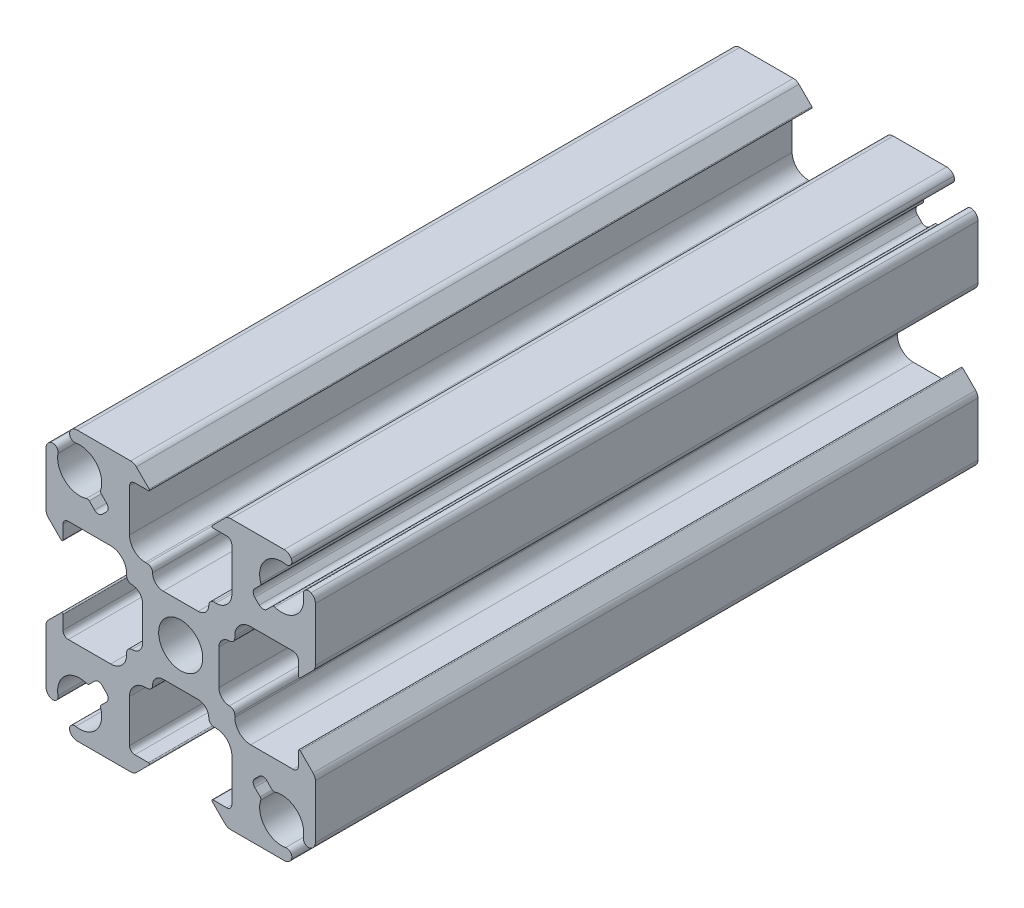
SolidWorks part; units mm, degrees
ref_plane "Front Plane" through (0, 0, 0) normal (0, 0, 1) x (1, 0, 0)
ref_plane "Top Plane" through (0, 0, 0) normal (0, 1, 0) x (1, 0, 0)
ref_plane "Right Plane" through (0, 0, 0) normal (1, 0, 0) x (0, 0, -1)
ref_plane "Plane1" through (0, 0, 0) normal (0, 0, -1) x (-1, 0, 0)
sketch "Sketch1" plane through (0, 0, 0) normal (0, 0, -1) x (-1, 0, 0)
  line L0 (-7.4885, 8.6199) -> (-6.9856, 8.117)
  line L1 (-6.9856, 7.4099) -> (-7.4099, 6.9856)
  line L2 (-8.117, 6.9856) -> (-8.6199, 7.4885)
  line L3 (-12.7, 9.7594) -> (-12.7, 4.7107)
  line L4 (-12.4803, 4.1803) -> (-11.2707, 2.9707)
  line L5 (-11.1, 3.0414) -> (-11.1, 4.325)
  line L6 (-10.6, 4.825) -> (-6.6, 4.825)
  line L7 (-5.1, 3.325) -> (-5.1, 3.15)
  line L8 (-3.6, 1.65) -> (-3.6, -1.65)
  line L9 (-5.1, -3.15) -> (-5.1, -3.325)
  line L10 (-6.6, -4.825) -> (-10.6, -4.825)
  line L11 (-11.1, -4.325) -> (-11.1, -3.0414)
  line L12 (-11.2707, -2.9707) -> (-12.4803, -4.1803)
  line L13 (-12.7, -4.7107) -> (-12.7, -9.7594)
  line L14 (-8.6199, -7.4885) -> (-8.117, -6.9856)
  line L15 (-7.4099, -6.9856) -> (-6.9856, -7.4099)
  line L16 (-6.9856, -8.117) -> (-7.4885, -8.6199)
  line L17 (-9.7594, -12.7) -> (-4.7107, -12.7)
  line L18 (-4.1803, -12.4803) -> (-2.9707, -11.2707)
  line L19 (-3.0414, -11.1) -> (-4.325, -11.1)
  line L20 (-4.825, -10.6) -> (-4.825, -6.6)
  line L21 (-3.325, -5.1) -> (-3.15, -5.1)
  line L22 (-1.65, -3.6) -> (1.65, -3.6)
  line L23 (3.15, -5.1) -> (3.325, -5.1)
  line L24 (4.825, -6.6) -> (4.825, -10.6)
  line L25 (4.325, -11.1) -> (3.0414, -11.1)
  line L26 (2.9707, -11.2707) -> (4.1803, -12.4803)
  line L27 (4.7107, -12.7) -> (9.7594, -12.7)
  line L28 (7.4885, -8.6199) -> (6.9856, -8.117)
  line L29 (6.9856, -7.4099) -> (7.4099, -6.9856)
  line L30 (8.117, -6.9856) -> (8.6199, -7.4885)
  line L31 (12.7, -9.7594) -> (12.7, -4.7107)
  line L32 (12.4803, -4.1803) -> (11.2707, -2.9707)
  line L33 (11.1, -3.0414) -> (11.1, -4.325)
  line L34 (10.6, -4.825) -> (6.6, -4.825)
  line L35 (5.1, -3.325) -> (5.1, -3.15)
  line L36 (3.6, -1.65) -> (3.6, 1.65)
  line L37 (5.1, 3.15) -> (5.1, 3.325)
  line L38 (6.6, 4.825) -> (10.6, 4.825)
  line L39 (11.1, 4.325) -> (11.1, 3.0414)
  line L40 (11.2707, 2.9707) -> (12.4803, 4.1803)
  line L41 (12.7, 4.7107) -> (12.7, 9.7594)
  line L42 (8.6199, 7.4885) -> (8.117, 6.9856)
  line L43 (7.4099, 6.9856) -> (6.9856, 7.4099)
  line L44 (6.9856, 8.117) -> (7.4885, 8.6199)
  line L45 (9.7594, 12.7) -> (4.7107, 12.7)
  line L46 (4.1803, 12.4803) -> (2.9707, 11.2707)
  line L47 (3.0414, 11.1) -> (4.325, 11.1)
  line L48 (4.825, 10.6) -> (4.825, 6.6)
  line L49 (3.325, 5.1) -> (3.15, 5.1)
  line L50 (1.65, 3.6) -> (-1.65, 3.6)
  line L51 (-3.15, 5.1) -> (-3.325, 5.1)
  line L52 (-4.825, 6.6) -> (-4.825, 10.6)
  line L53 (-4.325, 11.1) -> (-3.0414, 11.1)
  line L54 (-2.9707, 11.2707) -> (-4.1803, 12.4803)
  line L55 (-4.7107, 12.7) -> (-9.7594, 12.7)
  circle A0 centre (0, 0) radius 2.08
  arc A1 (-9.7594, 12.7) -> (-10.4266, 12.2927) centre (-9.7594, 11.95) ccw
  arc A2 (-10.4266, 12.2927) -> (-9.8933, 11.5721) centre (-9.9818, 12.0642) ccw
  arc A3 (-9.8933, 11.5721) -> (-7.5492, 8.8748) centre (-9.525, 9.525) cw
  arc A4 (-7.5492, 8.8748) -> (-7.4885, 8.6199) centre (-7.3118, 8.7967) ccw
  arc A5 (-6.9856, 8.117) -> (-6.9856, 7.4099) centre (-7.3392, 7.7635) cw
  arc A6 (-7.4099, 6.9856) -> (-8.117, 6.9856) centre (-7.7635, 7.3392) cw
  arc A7 (-8.6199, 7.4885) -> (-8.8748, 7.5492) centre (-8.7967, 7.3118) ccw
  arc A8 (-8.8748, 7.5492) -> (-11.5721, 9.8933) centre (-9.525, 9.525) cw
  arc A9 (-11.5721, 9.8933) -> (-12.2927, 10.4266) centre (-12.0642, 9.9818) ccw
  arc A10 (-12.2927, 10.4266) -> (-12.7, 9.7594) centre (-11.95, 9.7594) ccw
  arc A11 (-12.7, 4.7107) -> (-12.4803, 4.1803) centre (-11.95, 4.7107) ccw
  arc A12 (-11.2707, 2.9707) -> (-11.1, 3.0414) centre (-11.2, 3.0414) ccw
  arc A13 (-11.1, 4.325) -> (-10.6, 4.825) centre (-10.6, 4.325) cw
  arc A14 (-6.6, 4.825) -> (-5.1, 3.325) centre (-6.6, 3.325) cw
  arc A15 (-5.1, 3.15) -> (-4.6, 2.65) centre (-4.6, 3.15) ccw
  arc A16 (-4.6, 2.65) -> (-3.6, 1.65) centre (-4.6, 1.65) cw
  arc A17 (-3.6, -1.65) -> (-4.6, -2.65) centre (-4.6, -1.65) cw
  arc A18 (-4.6, -2.65) -> (-5.1, -3.15) centre (-4.6, -3.15) ccw
  arc A19 (-5.1, -3.325) -> (-6.6, -4.825) centre (-6.6, -3.325) cw
  arc A20 (-10.6, -4.825) -> (-11.1, -4.325) centre (-10.6, -4.325) cw
  arc A21 (-11.1, -3.0414) -> (-11.2707, -2.9707) centre (-11.2, -3.0414) ccw
  arc A22 (-12.4803, -4.1803) -> (-12.7, -4.7107) centre (-11.95, -4.7107) ccw
  arc A23 (-12.7, -9.7594) -> (-12.2927, -10.4266) centre (-11.95, -9.7594) ccw
  arc A24 (-12.2927, -10.4266) -> (-11.5721, -9.8933) centre (-12.0642, -9.9818) ccw
  arc A25 (-11.5721, -9.8933) -> (-8.8748, -7.5492) centre (-9.525, -9.525) cw
  arc A26 (-8.8748, -7.5492) -> (-8.6199, -7.4885) centre (-8.7967, -7.3118) ccw
  arc A27 (-8.117, -6.9856) -> (-7.4099, -6.9856) centre (-7.7635, -7.3392) cw
  arc A28 (-6.9856, -7.4099) -> (-6.9856, -8.117) centre (-7.3392, -7.7635) cw
  arc A29 (-7.4885, -8.6199) -> (-7.5492, -8.8748) centre (-7.3118, -8.7967) ccw
  arc A30 (-7.5492, -8.8748) -> (-9.8933, -11.5721) centre (-9.525, -9.525) cw
  arc A31 (-9.8933, -11.5721) -> (-10.4266, -12.2927) centre (-9.9818, -12.0642) ccw
  arc A32 (-10.4266, -12.2927) -> (-9.7594, -12.7) centre (-9.7594, -11.95) ccw
  arc A33 (-4.7107, -12.7) -> (-4.1803, -12.4803) centre (-4.7107, -11.95) ccw
  arc A34 (-2.9707, -11.2707) -> (-3.0414, -11.1) centre (-3.0414, -11.2) ccw
  arc A35 (-4.325, -11.1) -> (-4.825, -10.6) centre (-4.325, -10.6) cw
  arc A36 (-4.825, -6.6) -> (-3.325, -5.1) centre (-3.325, -6.6) cw
  arc A37 (-3.15, -5.1) -> (-2.65, -4.6) centre (-3.15, -4.6) ccw
  arc A38 (-2.65, -4.6) -> (-1.65, -3.6) centre (-1.65, -4.6) cw
  arc A39 (1.65, -3.6) -> (2.65, -4.6) centre (1.65, -4.6) cw
  arc A40 (2.65, -4.6) -> (3.15, -5.1) centre (3.15, -4.6) ccw
  arc A41 (3.325, -5.1) -> (4.825, -6.6) centre (3.325, -6.6) cw
  arc A42 (4.825, -10.6) -> (4.325, -11.1) centre (4.325, -10.6) cw
  arc A43 (3.0414, -11.1) -> (2.9707, -11.2707) centre (3.0414, -11.2) ccw
  arc A44 (4.1803, -12.4803) -> (4.7107, -12.7) centre (4.7107, -11.95) ccw
  arc A45 (9.7594, -12.7) -> (10.4266, -12.2927) centre (9.7594, -11.95) ccw
  arc A46 (10.4266, -12.2927) -> (9.8933, -11.5721) centre (9.9818, -12.0642) ccw
  arc A47 (9.8933, -11.5721) -> (7.5492, -8.8748) centre (9.525, -9.525) cw
  arc A48 (7.5492, -8.8748) -> (7.4885, -8.6199) centre (7.3118, -8.7967) ccw
  arc A49 (6.9856, -8.117) -> (6.9856, -7.4099) centre (7.3392, -7.7635) cw
  arc A50 (7.4099, -6.9856) -> (8.117, -6.9856) centre (7.7635, -7.3392) cw
  arc A51 (8.6199, -7.4885) -> (8.8748, -7.5492) centre (8.7967, -7.3118) ccw
  arc A52 (8.8748, -7.5492) -> (11.5721, -9.8933) centre (9.525, -9.525) cw
  arc A53 (11.5721, -9.8933) -> (12.2927, -10.4266) centre (12.0642, -9.9818) ccw
  arc A54 (12.2927, -10.4266) -> (12.7, -9.7594) centre (11.95, -9.7594) ccw
  arc A55 (12.7, -4.7107) -> (12.4803, -4.1803) centre (11.95, -4.7107) ccw
  arc A56 (11.2707, -2.9707) -> (11.1, -3.0414) centre (11.2, -3.0414) ccw
  arc A57 (11.1, -4.325) -> (10.6, -4.825) centre (10.6, -4.325) cw
  arc A58 (6.6, -4.825) -> (5.1, -3.325) centre (6.6, -3.325) cw
  arc A59 (5.1, -3.15) -> (4.6, -2.65) centre (4.6, -3.15) ccw
  arc A60 (4.6, -2.65) -> (3.6, -1.65) centre (4.6, -1.65) cw
  arc A61 (3.6, 1.65) -> (4.6, 2.65) centre (4.6, 1.65) cw
  arc A62 (4.6, 2.65) -> (5.1, 3.15) centre (4.6, 3.15) ccw
  arc A63 (5.1, 3.325) -> (6.6, 4.825) centre (6.6, 3.325) cw
  arc A64 (10.6, 4.825) -> (11.1, 4.325) centre (10.6, 4.325) cw
  arc A65 (11.1, 3.0414) -> (11.2707, 2.9707) centre (11.2, 3.0414) ccw
  arc A66 (12.4803, 4.1803) -> (12.7, 4.7107) centre (11.95, 4.7107) ccw
  arc A67 (12.7, 9.7594) -> (12.2927, 10.4266) centre (11.95, 9.7594) ccw
  arc A68 (12.2927, 10.4266) -> (11.5721, 9.8933) centre (12.0642, 9.9818) ccw
  arc A69 (11.5721, 9.8933) -> (8.8748, 7.5492) centre (9.525, 9.525) cw
  arc A70 (8.8748, 7.5492) -> (8.6199, 7.4885) centre (8.7967, 7.3118) ccw
  arc A71 (8.117, 6.9856) -> (7.4099, 6.9856) centre (7.7635, 7.3392) cw
  arc A72 (6.9856, 7.4099) -> (6.9856, 8.117) centre (7.3392, 7.7635) cw
  arc A73 (7.4885, 8.6199) -> (7.5492, 8.8748) centre (7.3118, 8.7967) ccw
  arc A74 (7.5492, 8.8748) -> (9.8933, 11.5721) centre (9.525, 9.525) cw
  arc A75 (9.8933, 11.5721) -> (10.4266, 12.2927) centre (9.9818, 12.0642) ccw
  arc A76 (10.4266, 12.2927) -> (9.7594, 12.7) centre (9.7594, 11.95) ccw
  arc A77 (4.7107, 12.7) -> (4.1803, 12.4803) centre (4.7107, 11.95) ccw
  arc A78 (2.9707, 11.2707) -> (3.0414, 11.1) centre (3.0414, 11.2) ccw
  arc A79 (4.325, 11.1) -> (4.825, 10.6) centre (4.325, 10.6) cw
  arc A80 (4.825, 6.6) -> (3.325, 5.1) centre (3.325, 6.6) cw
  arc A81 (3.15, 5.1) -> (2.65, 4.6) centre (3.15, 4.6) ccw
  arc A82 (2.65, 4.6) -> (1.65, 3.6) centre (1.65, 4.6) cw
  arc A83 (-1.65, 3.6) -> (-2.65, 4.6) centre (-1.65, 4.6) cw
  arc A84 (-2.65, 4.6) -> (-3.15, 5.1) centre (-3.15, 4.6) ccw
  arc A85 (-3.325, 5.1) -> (-4.825, 6.6) centre (-3.325, 6.6) cw
  arc A86 (-4.825, 10.6) -> (-4.325, 11.1) centre (-4.325, 10.6) cw
  arc A87 (-3.0414, 11.1) -> (-2.9707, 11.2707) centre (-3.0414, 11.2) ccw
  arc A88 (-4.1803, 12.4803) -> (-4.7107, 12.7) centre (-4.7107, 11.95) ccw
extrude "Boss-Extrude1" add sketch "Sketch1" against normal mid plane 62.483
